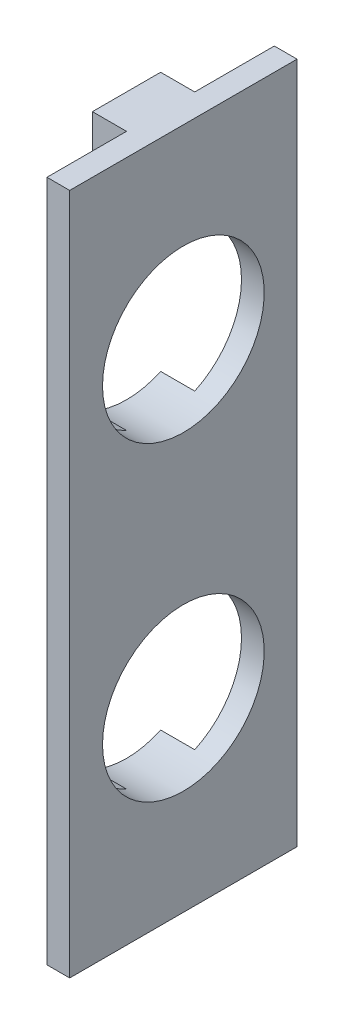
SolidWorks part; units mm, degrees
ref_plane "Front Plane" through (0, 0, 0) normal (0, 0, 1) x (1, 0, 0)
ref_plane "Top Plane" through (0, 0, 0) normal (0, 1, 0) x (1, 0, 0)
ref_plane "Right Plane" through (0, 0, 0) normal (1, 0, 0) x (0, 0, -1)
sketch "Sketch1" plane through (0, 0, 0) normal (0, 1, 0) x (1, 0, 0)
  line L0 (-1.6261, 3) -> (-1.6261, 6.5)
  line L1 (-1.6261, 6.5) -> (-0.6261, 6.5)
  line L2 (-0.6261, 6.5) -> (-0.6261, -3.5)
  line L4 (-3.1261, 3) -> (-1.6261, 3)
  line L7 (-0.6261, -3.5) -> (-1.6261, -3.5)
  line L8 (-1.6261, -3.5) -> (-1.6261, 0)
  line L9 (-1.6261, 0) -> (-3.1261, 0)
  line L10 (-3.1261, 0) -> (-3.1261, 3)
  dimension "D1" = 3
  dimension "D2" = 10
  dimension "D3" = 3.5
  dimension "D5" = 1
  dimension "D6" = 1
  dimension "D7" = 1.5
extrude "Boss-Extrude1" add sketch "Sketch1" along normal blind 30
sketch "Sketch2" plane through (-3.1261, 0, 0) normal (-1, 0, 0) x (0, 0, 1)
  circle A0 centre (-1.5, 21.83) radius 3.556
  circle A1 centre (-1.5, 8.17) radius 3.556
extrude "Cut-Extrude1" cut sketch "Sketch2" against normal blind 30
